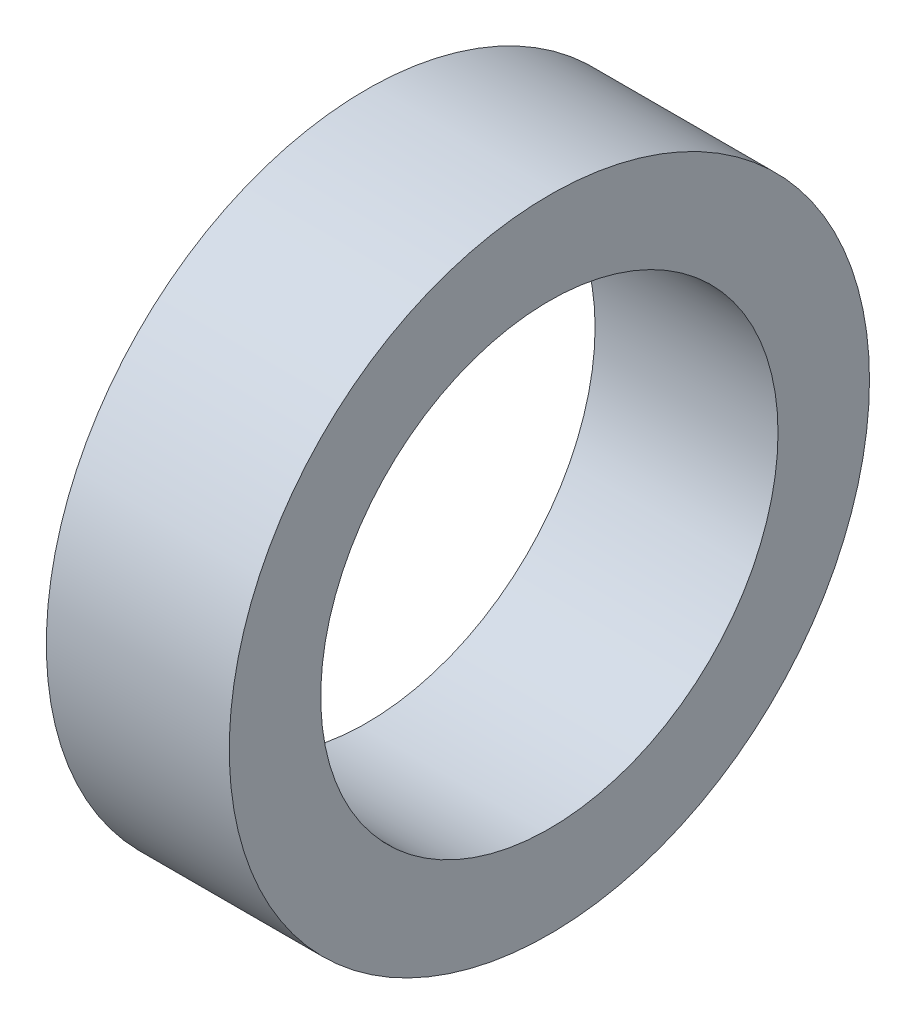
SolidWorks part; units mm, degrees
ref_plane "Front Plane" through (0, 0, 0) normal (0, 0, 1) x (1, 0, 0)
ref_plane "Top Plane" through (0, 0, 0) normal (0, 1, 0) x (1, 0, 0)
ref_plane "Right Plane" through (0, 0, 0) normal (1, 0, 0) x (0, 0, -1)
sketch "Sketch1" plane through (0, 0, 0) normal (1, 0, 0) x (0, 0, -1)
  circle A0 centre (0, 0) radius 25
  circle A1 centre (0, 0) radius 35
  dimension "D1" = 50
  dimension "D2" = 70
extrude "Boss-Extrude1" add sketch "Sketch1" along normal blind 20
